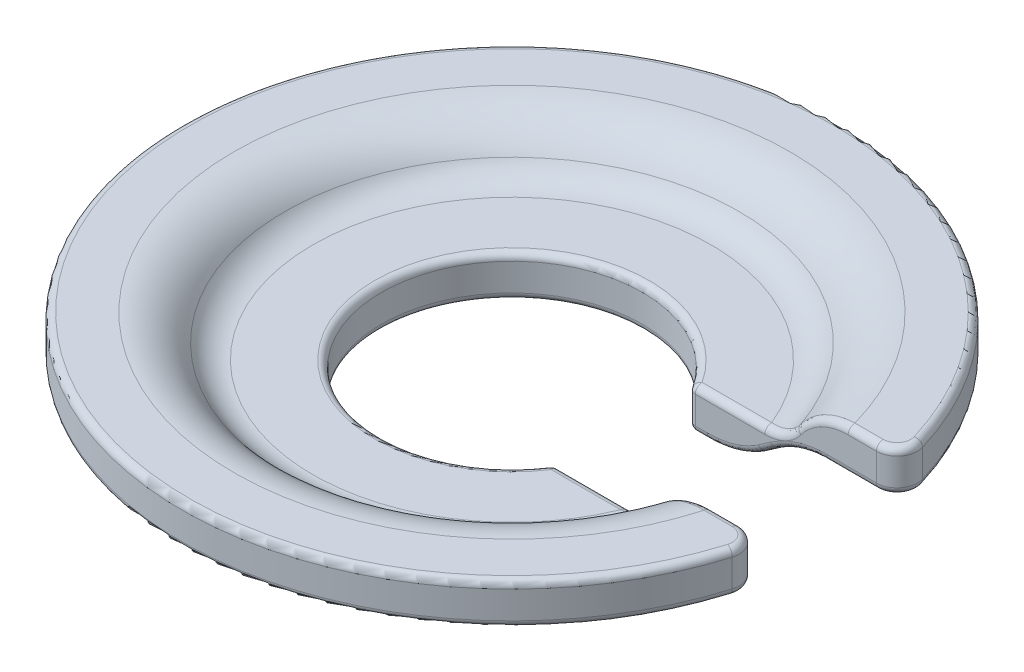
SolidWorks part; units mm, degrees
material "Ductile Iron"
ref_plane "Front Plane" through (0, 0, 0) normal (0, 0, 1) x (1, 0, 0)
ref_plane "Top Plane" through (0, 0, 0) normal (0, 1, 0) x (1, 0, 0)
ref_plane "Right Plane" through (0, 0, 0) normal (1, 0, 0) x (0, 0, -1)
sketch "Sketch1" plane through (0, 0, 0) normal (0, 0, 1) x (1, 0, 0)
  line L0 (0, 0) -> (24, 0) construction
  line L1 (9.5, 0) -> (10.75, 0)
  line L2 (18.75, 3) -> (24, 3)
  line L3 (9.5, 0) -> (9.5, 3)
  line L4 (9.5, 3) -> (14.5, 3)
  line L5 (20.2446, 6) -> (24, 6)
  line L6 (24, 6) -> (24, 3)
  line L7 (0, 0) -> (0, 4.9633) construction
  arc A0 (10.75, 0) -> (14.3605, 1.2079) centre (10.75, 6) ccw
  arc A1 (14.3605, 1.2079) -> (15.1608, 1.8081) centre (149.755, -178.4956) cw
  arc A2 (15.1608, 1.8081) -> (18.75, 3) centre (18.75, -3) cw
  arc A3 (14.5, 3) -> (16.5516, 4.0714) centre (14.5, 5.5) ccw
  arc A4 (16.5516, 4.0714) -> (20.2446, 6) centre (20.2446, 1.5) cw
  point P3 (9.5, 0)
  dimension "D3" = 3
  dimension "D4" = 5.25
  dimension "D6" = 6
  dimension "D7" = 3
  dimension "D10" = 2.5
  dimension "D11" = 4.5
  dimension "D12" = 225
  dimension "D1" = 24
  dimension "D2" = 9.5
  dimension "D5" = 1.25
  dimension "D8" = 14.5
  dimension "D9" = 3
revolve "Revolve1" add sketch "Sketch1" angle 360 about L7
sketch "Sketch2" plane through (0, 6, 0) normal (0, 1, 0) x (1, 0, 0)
  line L1 (0, -5) -> (25, -5)
  line L2 (0, -5) -> (0, 5)
  line L3 (0, 5) -> (25, 5)
  line L4 (25, -5) -> (25, 5)
  line L5 (0, -5) -> (25, 5) construction
  line L6 (0, 5) -> (25, -5) construction
  point P0 (12.5, 0)
  dimension "D1" = 10
  dimension "D2" = 25
  dimension "D3" = 0
extrude "Cut-Extrude1" cut sketch "Sketch2" against normal through all
fillet "Fillet1" radius 1.5 2 edges at (23.4734, 4.5, 5) (23.4734, 4.5, -5)
fillet "Fillet2" radius 0.5 28 edges at (10.8442, 3, 5) (14.2394, 3.071, 5) (21.6523, -2.5422, 5) (20.579, 6, 5) (22.7448, 6, 5.6056) (10.8442, 3, -5) (14.8464, 3.2884, -5) (22.1722, -2.252, -5) (20.579, 6, -5) (22.7448, 6, -5.6056) (8.7971, 0, 5) (12.23, 0.5286, 5) (16.4811, 2.8024, 5) (19.8058, 3, 5) (22.7448, 3, 5.6056) (8.7971, 0, -5) (12.1917, 0.5128, -5) (19.8058, 3, -5) (22.7448, 3, -5.6056) (-9.5, 3, 0) (8.0777, 1.5, -5) (-9.5, 0, 0) (8.0777, 1.5, 5) (-24, 6, 0) (-24, 3, 0)
sketch "Sketch3" plane through (0, 3, 0) normal (0, -1, 0) x (1, 0, 0)
  point P0 (0, 0)
